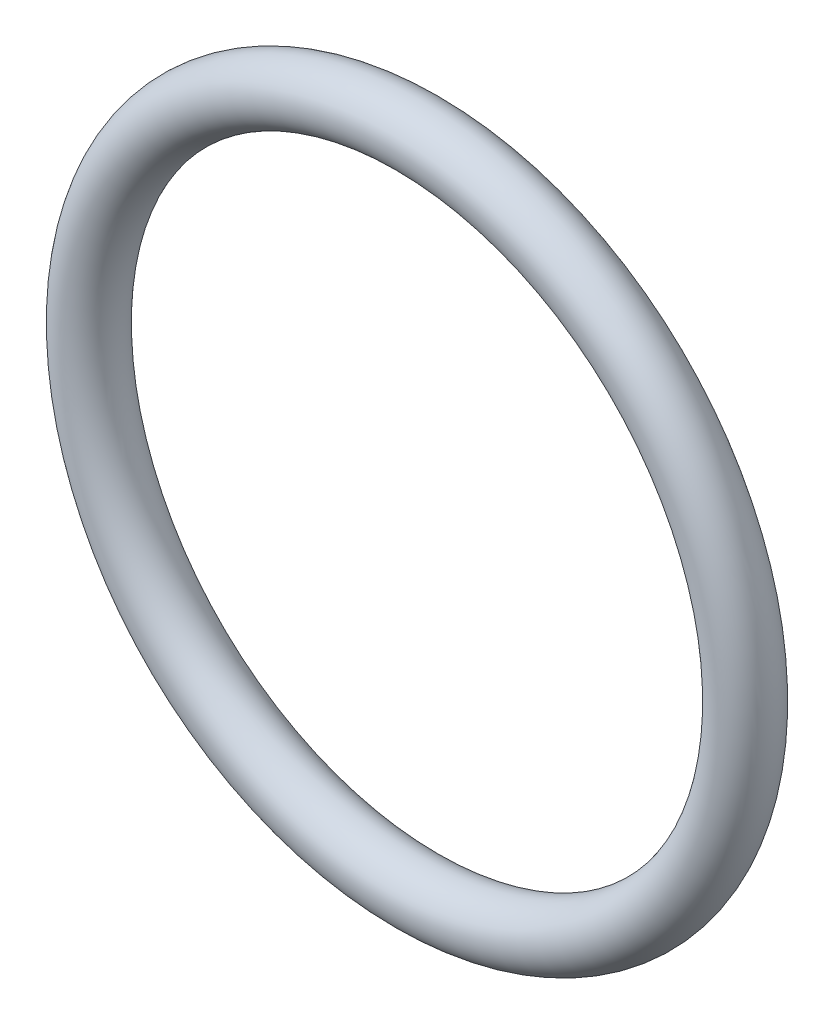
SolidWorks part; units mm, degrees
ref_plane "Front Plane" through (0, 0, 0) normal (0, 0, 1) x (1, 0, 0)
ref_plane "Top Plane" through (0, 0, 0) normal (0, 1, 0) x (1, 0, 0)
ref_plane "Right Plane" through (0, 0, 0) normal (1, 0, 0) x (0, 0, -1)
sketch "Sketch1" plane through (0, 0, 0) normal (1, 0, 0) x (0, 0, -1)
  line L0 (0, -34.6075) -> (0, 34.6075) construction
  circle A0 centre (0, -38.1) radius 3.4925 construction
  circle A1 centre (0, 38.1) radius 3.4925 construction
  point P3 (-3.4925, -34.6075)
  point P4 (0, 0)
  point P7 (0, -41.5925)
  point P8 (-3.4925, -38.1)
  point P9 (3.4925, -38.1)
  point P12 (0, 41.5925)
  dimension "ID" = 69.215
  dimension "OD" = 83.185
  dimension "Width" = 6.985
sketch "Sketch2" plane through (0, 0, 0) normal (1, 0, 0) x (0, 0, -1)
  line L0 (-34.6075, 0) -> (34.6075, 0) construction
  line L1 (0, -34.6075) -> (0, 34.6075) construction
  circle A0 centre (0, 38.1) radius 3.4925 construction
  circle A1 centre (0, 38.1) radius 3.4925
  point P7 (0, 0)
revolve "Revolve1" add sketch "Sketch2" angle 360 about L0
sketch "Drawing Reference 1" plane through (0, 0, 0) normal (0, 0, 1) x (1, 0, 0)
  circle A0 centre (0, 0) radius 41.5925
  circle A1 centre (0, 0) radius 34.6075
sketch "Sketch3" plane through (0, 0, 0) normal (0, 0, 1) x (1, 0, 0)
  circle A0 centre (0, 0) radius 41.5925
  dimension "D1" = 83.185
